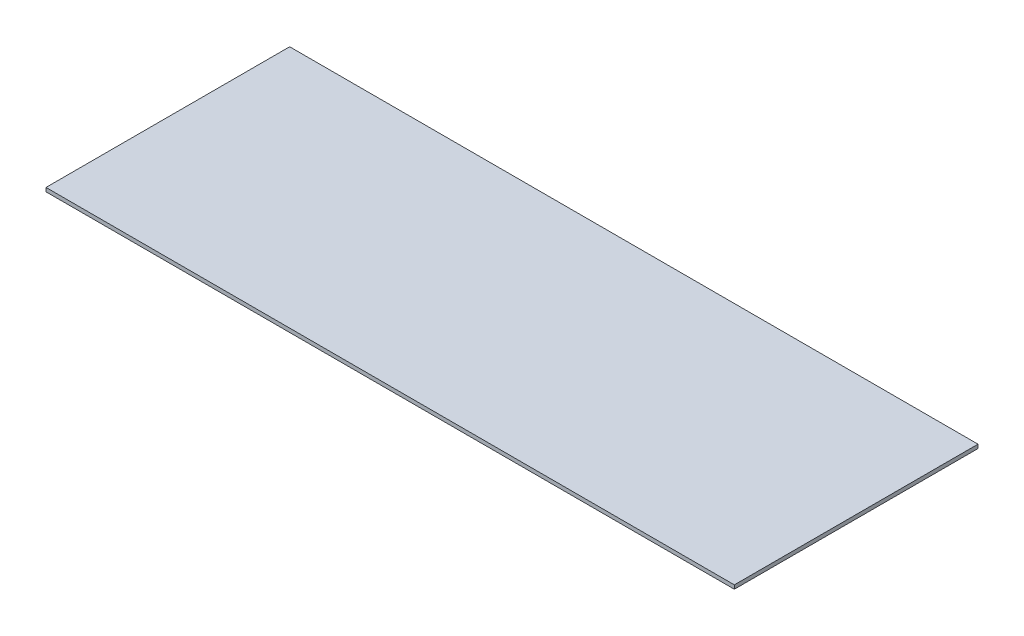
SolidWorks part; units mm, degrees
material "1060 Alloy"
ref_plane "Front" through (0, 0, 0) normal (0, 0, 1) x (1, 0, 0)
ref_plane "Top" through (0, 0, 0) normal (0, 1, 0) x (1, 0, 0)
ref_plane "Right" through (0, 0, 0) normal (1, 0, 0) x (0, 0, -1)
sketch "Sketch1" plane through (0, 0, 0) normal (0, 1, 0) x (1, 0, 0)
  line L1 (0, 0) -> (228.727, 0)
  line L2 (0, 0) -> (0, 80.9625)
  line L3 (0, 80.9625) -> (228.727, 80.9625)
  line L4 (228.727, 0) -> (228.727, 80.9625)
  dimension "D1" = 80.9625
  dimension "D2" = 228.727
extrude "Boss-Extrude1" add sketch "Sketch1" along normal blind 1.27
